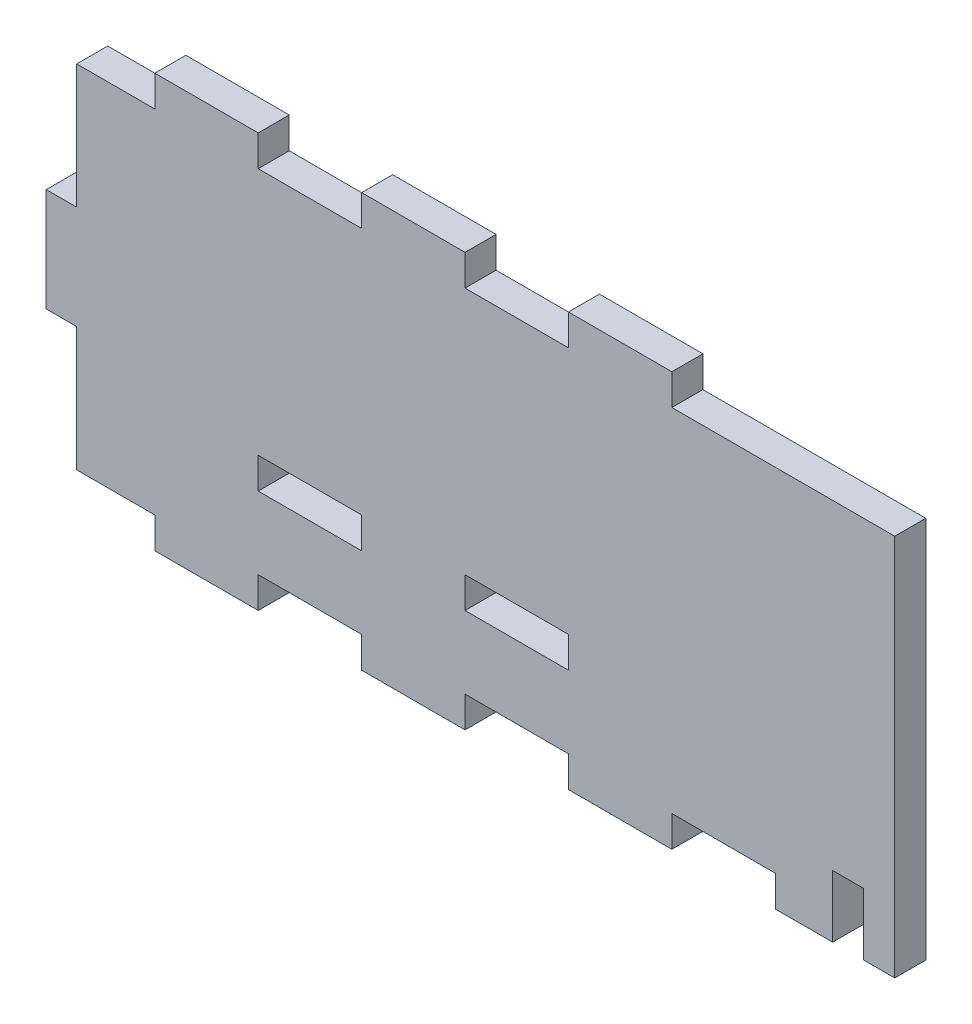
SolidWorks part; units mm, degrees
ref_plane "前基準面" through (0, 0, 0) normal (0, 0, 1) x (1, 0, 0)
ref_plane "上基準面" through (0, 0, 0) normal (0, 1, 0) x (1, 0, 0)
ref_plane "右基準面" through (0, 0, 0) normal (1, 0, 0) x (0, 0, -1)
sketch "草圖1" plane through (0, 0, 0) normal (0, 0, 1) x (1, 0, 0)
  line L0 (-43.5889, -2.1676) -> (27.4111, -2.1676) construction
  line L1 (-43.5889, 17.8324) -> (27.4111, 17.8324) construction
  line L2 (-43.5889, 17.8324) -> (-43.5889, -22.1676) construction
  line L3 (-43.5889, -22.1676) -> (27.4111, -22.1676) construction
  line L4 (27.4111, 17.8324) -> (27.4111, -22.1676) construction
  line L5 (-8.0889, 17.8324) -> (-8.0889, -22.1676) construction
  line L6 (6.9111, 14.8324) -> (16.9111, 14.8324)
  line L7 (27.4111, 2.8324) -> (24.4111, 2.8324)
  line L8 (27.4111, 2.8324) -> (27.4111, -7.1676)
  line L9 (27.4111, -7.1676) -> (24.4111, -7.1676)
  line L11 (-13.0889, 17.8324) -> (-3.0889, 17.8324)
  line L12 (-13.0889, 17.8324) -> (-13.0889, 14.8324)
  line L13 (-13.0889, 14.8324) -> (-3.0889, 14.8324)
  line L14 (-3.0889, 17.8324) -> (-3.0889, 14.8324)
  line L15 (-23.0889, 17.8324) -> (-33.0889, 17.8324)
  line L16 (-23.0889, 17.8324) -> (-23.0889, 14.8324)
  line L17 (-23.0889, 14.8324) -> (-33.0889, 14.8324)
  line L18 (-33.0889, 17.8324) -> (-33.0889, 14.8324)
  line L19 (16.9111, 17.8324) -> (16.9111, 14.8324)
  line L20 (6.9111, 17.8324) -> (16.9111, 17.8324)
  line L21 (6.9111, 17.8324) -> (6.9111, 14.8324)
  line L22 (-43.5889, -7.1676) -> (-40.5889, -7.1676)
  line L24 (-43.5889, 2.8324) -> (-40.5889, 2.8324)
  line L25 (-43.5889, 2.8324) -> (-43.5889, -7.1676)
  line L26 (6.9111, -22.1676) -> (6.9111, -19.1676)
  line L27 (6.9111, -22.1676) -> (16.9111, -22.1676)
  line L28 (16.9111, -22.1676) -> (16.9111, -19.1676)
  line L29 (6.9111, -19.1676) -> (16.9111, -19.1676)
  line L30 (-13.0889, -19.1676) -> (-3.0889, -19.1676)
  line L31 (-3.0889, -22.1676) -> (-3.0889, -19.1676)
  line L32 (-13.0889, -22.1676) -> (-3.0889, -22.1676)
  line L33 (-13.0889, -22.1676) -> (-13.0889, -19.1676)
  line L34 (-23.0889, -19.1676) -> (-33.0889, -19.1676)
  line L35 (-33.0889, -22.1676) -> (-33.0889, -19.1676)
  line L36 (-23.0889, -22.1676) -> (-33.0889, -22.1676)
  line L37 (-23.0889, -22.1676) -> (-23.0889, -19.1676)
  line L38 (-40.6424, -7.1676) -> (-40.6424, -19.1676)
  line L39 (-40.6424, 14.8324) -> (24.4645, 14.8324)
  line L40 (-40.6424, 14.8324) -> (-40.6424, 2.8324)
  line L41 (-40.6424, -19.1676) -> (24.4645, -19.1676)
  line L42 (24.4645, 14.8324) -> (24.4645, 2.8324)
  line L43 (-40.6424, 14.8324) -> (24.4645, -19.1676) construction
  line L44 (-40.6424, -19.1676) -> (24.4645, 14.8324) construction
  line L45 (24.4645, -7.1676) -> (24.4645, -19.1676)
  point P12 (24.4111, -2.1676)
  point P13 (-8.0889, 14.8324)
  point P22 (-13.0889, 16.3324)
  point P43 (-8.0889, -2.1676)
  dimension "D1" = 71
  dimension "D2" = 40
  dimension "D3" = 10
  dimension "D4" = 3
  dimension "D5" = 3
  dimension "D6" = 10
  dimension "D7" = 3
  dimension "D8" = 10
  dimension "D9" = 10
extrude "填料-伸長1" add sketch "草圖1" along normal blind 3
sketch "草圖2" plane through (0, 0, 3) normal (0, 0, 1) x (1, 0, 0)
  line L0 (6.9111, 14.8324) -> (6.9111, -19.1676) construction
  line L1 (-8.0889, 17.8324) -> (-8.0889, -22.1676) construction
  line L2 (-13.0889, 17.8324) -> (-3.0889, 17.8324) construction
  line L3 (-13.0889, -22.1676) -> (-3.0889, -22.1676) construction
  line L5 (6.9111, -9.1676) -> (-3.0889, -9.1676)
  line L6 (6.9111, -9.1676) -> (6.9111, -12.1676)
  line L7 (6.9111, -12.1676) -> (-3.0889, -12.1676)
  line L8 (-3.0889, -9.1676) -> (-3.0889, -12.1676)
  line L9 (-23.0889, -12.1676) -> (-13.0889, -12.1676)
  line L10 (-13.0889, -9.1676) -> (-13.0889, -12.1676)
  line L11 (-23.0889, -9.1676) -> (-13.0889, -9.1676)
  line L12 (-23.0889, -9.1676) -> (-23.0889, -12.1676)
  line L13 (-3.0889, -19.1676) -> (6.9111, -19.1676) construction
  dimension "D1" = 3
  dimension "D2" = 10
  dimension "D3" = 7
extrude "除料-伸長1" cut sketch "草圖2" against normal blind 3
sketch "草圖3" plane through (0, 0, 3) normal (0, 0, 1) x (1, 0, 0)
  line L0 (16.9111, -19.1676) -> (24.4645, -19.1676) construction
  line L1 (24.4645, 14.8324) -> (38.4645, 14.8324)
  line L2 (24.4645, 14.8324) -> (24.4645, -19.1676)
  line L3 (24.4645, -19.1676) -> (38.4645, -19.1676)
  line L4 (38.4645, 14.8324) -> (38.4645, -19.1676)
  dimension "D1" = 14
extrude "填料-伸長3" add sketch "草圖3" against normal blind 3
sketch "草圖4" plane through (0, 0, 0) normal (0, 0, -1) x (-1, 0, 0)
  line L1 (-35.4645, -16.1676) -> (-32.4645, -16.1676)
  line L2 (-35.4645, -16.1676) -> (-35.4645, -19.1676)
  line L3 (-35.4645, -19.1676) -> (-32.4645, -19.1676)
  line L4 (-32.4645, -16.1676) -> (-32.4645, -19.1676)
  line L5 (-38.4645, -19.1676) -> (-38.4645, 14.8324) construction
  line L6 (-16.9111, -19.1676) -> (-38.4645, -19.1676) construction
  dimension "D1" = 3
  dimension "D2" = 3
  dimension "D3" = 3
extrude "除料-伸長2" cut sketch "草圖4" against normal blind 3
sketch "草圖5" plane through (0, 0, 0) normal (0, 0, -1) x (-1, 0, 0)
  line L0 (-16.9111, -22.1676) -> (-16.9111, -19.1676) construction
  line L1 (-38.4645, -19.1676) -> (-35.4645, -19.1676)
  line L2 (-38.4645, -19.1676) -> (-38.4645, -22.1676)
  line L3 (-38.4645, -22.1676) -> (-35.4645, -22.1676)
  line L4 (-35.4645, -19.1676) -> (-35.4645, -22.1676)
  line L5 (-32.4645, -19.1676) -> (-26.9111, -19.1676)
  line L6 (-32.4645, -19.1676) -> (-32.4645, -22.1676)
  line L7 (-32.4645, -22.1676) -> (-26.9111, -22.1676)
  line L8 (-26.9111, -19.1676) -> (-26.9111, -22.1676)
  point P12 (-29.6878, -19.1676)
  dimension "D1" = 3
  dimension "D2" = 3
  dimension "D3" = 10
  dimension "D4" = 3
extrude "填料-伸長4" add sketch "草圖5" against normal blind 3
